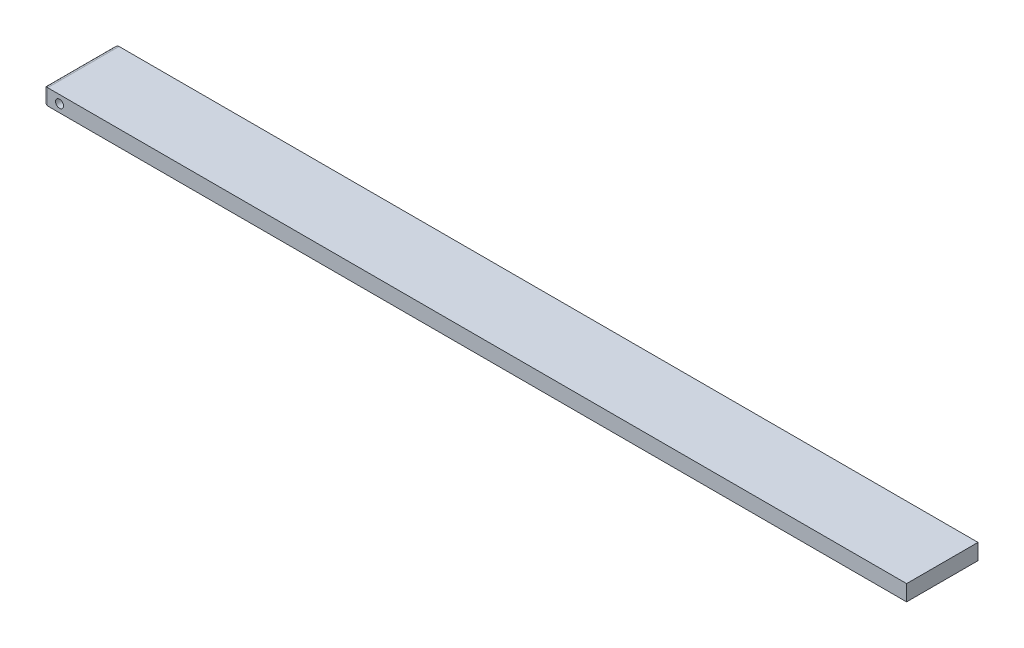
SolidWorks part; units mm, degrees
ref_plane "Front Plane" through (0, 0, 0) normal (0, 0, 1) x (1, 0, 0)
ref_plane "Top Plane" through (0, 0, 0) normal (0, 1, 0) x (1, 0, 0)
ref_plane "Right Plane" through (0, 0, 0) normal (1, 0, 0) x (0, 0, -1)
sketch "Sketch1" plane through (0, 0, 0) normal (0, 0, 1) x (1, 0, 0)
  line L0 (-30.9339, 0.0857) -> (20.0661, 0.0857) construction
  line L1 (-30.9339, 1.0857) -> (20.0661, 1.0857)
  line L2 (-30.9339, 1.0857) -> (-30.9339, -0.9143)
  line L3 (-30.9339, -0.9143) -> (20.0661, -0.9143)
  line L4 (20.0661, 1.0857) -> (20.0661, -0.9143)
  line L5 (-5.4339, 1.0857) -> (-5.4339, -0.9143) construction
  circle A0 centre (-28.9339, 0.0857) radius 0.5
  point P7 (-30.9339, 0.0857)
  dimension "D3" = 2
  dimension "D4" = 1
  dimension "D1" = 2
  dimension "D2" = 51
extrude "Boss-Extrude1" add sketch "Sketch1" along normal blind 9
fillet "Fillet2" radius 0.5 4 edges at (-30.9339, 1.0857, 4.5) (-30.9339, 0.0857, 9) (-30.9339, -0.9143, 4.5) (-30.9339, 0.0857, 0)
sketch "Sketch2" plane through (20.0661, 0, 0) normal (1, 0, 0) x (0, 0, -1)
  line L4 (0, -0.9143) -> (0, 1.0857)
  line L5 (0, 1.0857) -> (-9, 1.0857)
  line L6 (-9, 1.0857) -> (-9, -0.9143)
  line L7 (-9, -0.9143) -> (0, -0.9143)
  line L8 (0, -0.9143) -> (0, 1.0857)
  line L9 (0, 1.0857) -> (-9, 1.0857)
  line L10 (-9, 1.0857) -> (-9, -0.9143)
  line L11 (-9, -0.9143) -> (0, -0.9143)
  dimension "D1" = 0
extrude "Boss-Extrude2" add sketch "Sketch2" along normal blind 5
sketch "Sketch3" plane through (0, 0, 9) normal (0, 0, 1) x (1, 0, 0)
  line L0 (25.0661, 1.0857) -> (-30.4339, 1.0857) construction
  line L1 (21.0661, 1.0857) -> (25.0661, 1.0857)
  line L2 (21.0661, 1.0857) -> (21.0661, -0.9143)
  line L3 (21.0661, -0.9143) -> (25.0661, -0.9143)
  line L4 (25.0661, 1.0857) -> (25.0661, -0.9143)
  dimension "D1" = 4
scale "Scale1" scale about centroid uniform scaling yes scale factor 1.9329
scale "Scale2" scale about centroid uniform scaling yes scale factor 1.5
sketch "Sketch4" plane through (77.8387, 0, 0) normal (1, 0, 0) x (0, 0, -1)
  line L4 (-17.5471, -2.8136) -> (8.5471, -2.8136)
  line L5 (8.5471, -2.8136) -> (8.5471, 2.9851)
  line L6 (8.5471, 2.9851) -> (-17.5471, 2.9851)
  line L7 (-17.5471, 2.9851) -> (-17.5471, -2.8136)
  line L8 (-17.5471, -2.8136) -> (8.5471, -2.8136)
  line L9 (8.5471, -2.8136) -> (8.5471, 2.9851)
  line L10 (8.5471, 2.9851) -> (-17.5471, 2.9851)
  line L11 (-17.5471, 2.9851) -> (-17.5471, -2.8136)
  dimension "D1" = 0
extrude "Boss-Extrude3" add sketch "Sketch4" along normal blind 130
sketch "Sketch5" plane through (207.8387, 0, 0) normal (1, 0, 0) x (0, 0, -1)
  line L4 (-17.5471, 2.9851) -> (-17.5471, -2.8136)
  line L5 (-17.5471, -2.8136) -> (8.5471, -2.8136)
  line L6 (8.5471, -2.8136) -> (8.5471, 2.9851)
  line L7 (8.5471, 2.9851) -> (-17.5471, 2.9851)
  line L8 (-17.5471, 2.9851) -> (-17.5471, -2.8136)
  line L9 (-17.5471, -2.8136) -> (8.5471, -2.8136)
  line L10 (8.5471, -2.8136) -> (8.5471, 2.9851)
  line L11 (8.5471, 2.9851) -> (-17.5471, 2.9851)
  dimension "D1" = 0
extrude "Boss-Extrude4" add sketch "Sketch5" along normal blind 23
